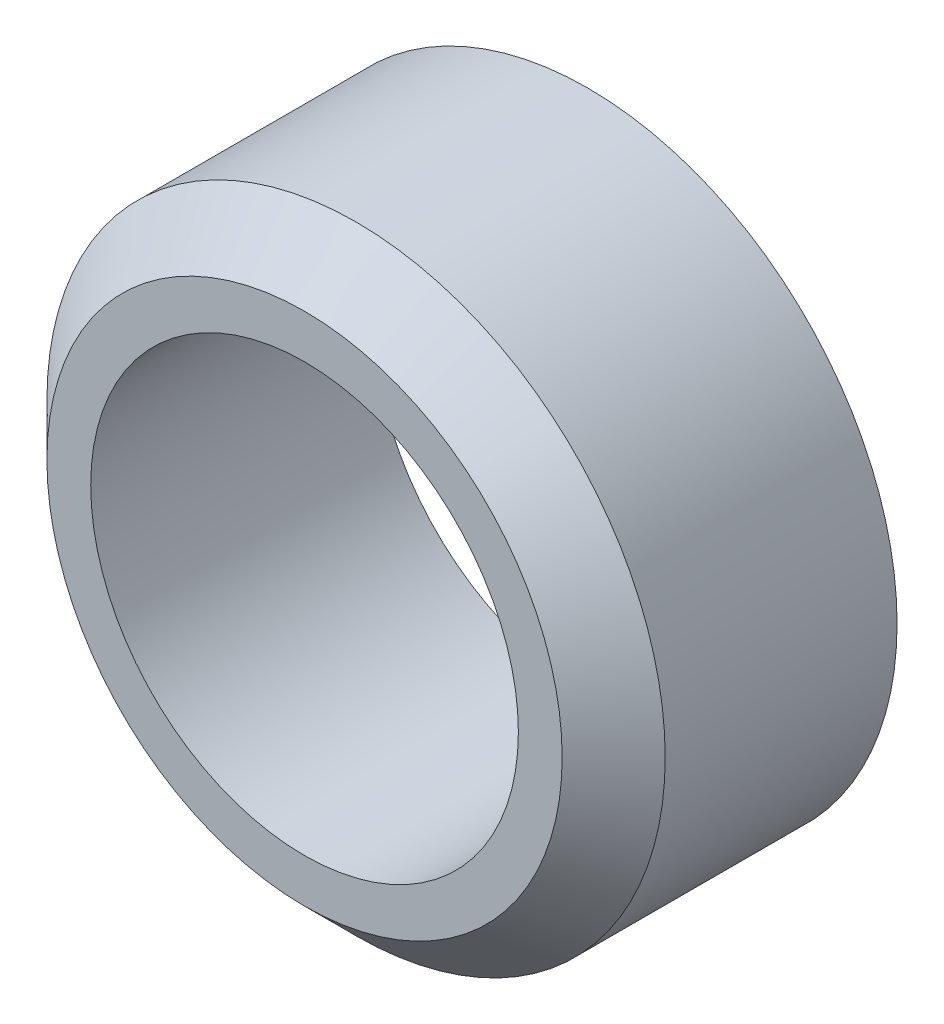
SolidWorks part; units mm, degrees
material "ﾎﾟﾘｴﾁﾚﾝｲﾐﾝ(PEI)"
ref_plane "正面" through (0, 0, 0) normal (0, 0, 1) x (1, 0, 0)
ref_plane "平面" through (0, 0, 0) normal (0, 1, 0) x (1, 0, 0)
ref_plane "右側面" through (0, 0, 0) normal (1, 0, 0) x (0, 0, -1)
sketch "ｽｹｯﾁ1" plane through (0, 0, 0) normal (0, 0, 1) x (1, 0, 0)
  circle A0 centre (0, 0) radius 6
  circle A1 centre (0, 0) radius 4.15
  dimension "D1" = 8.3
  dimension "D2" = 12
extrude "ﾎﾞｽ - 押し出し1" add sketch "ｽｹｯﾁ1" along normal blind 5.5
chamfer "面取り1" distance 1 angle 45 1 edges at (6, 0, 5.5)
